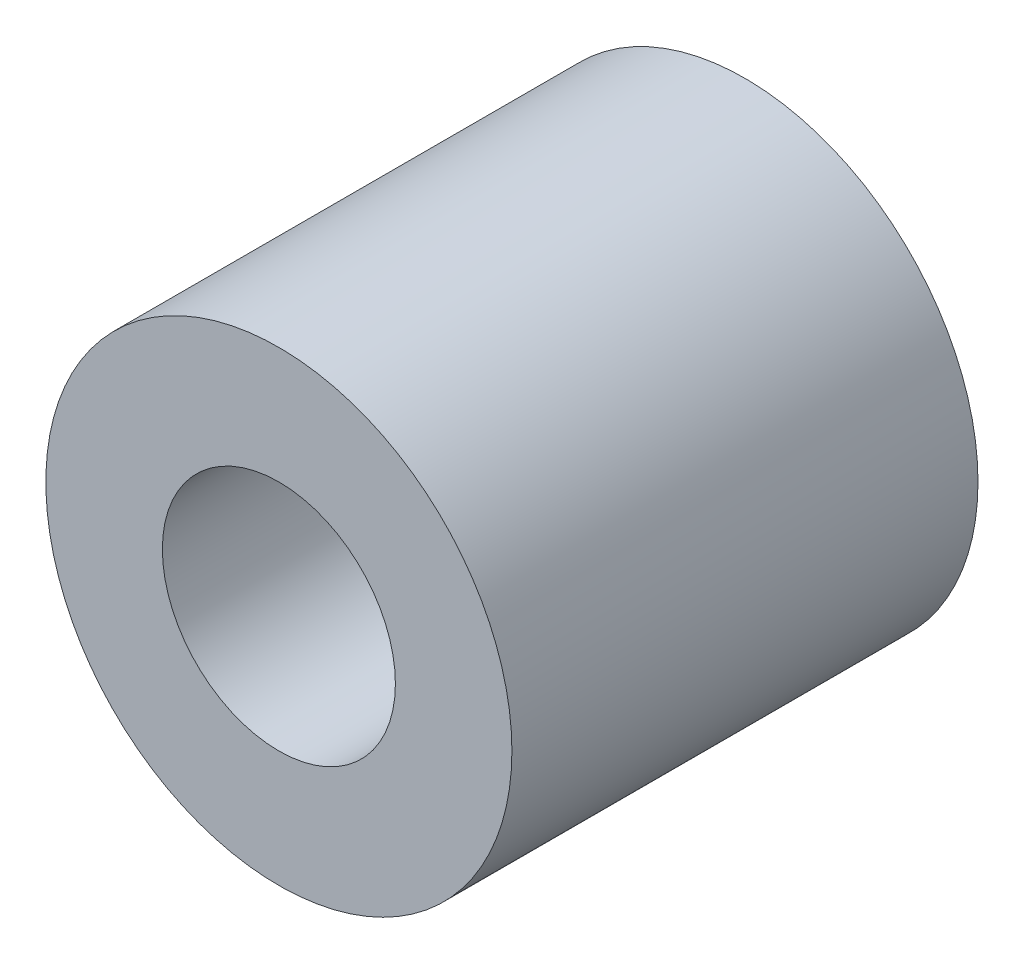
SolidWorks part; units mm, degrees
ref_plane "Front Plane" through (0, 0, 0) normal (0, 0, 1) x (1, 0, 0)
ref_plane "Top Plane" through (0, 0, 0) normal (0, 1, 0) x (1, 0, 0)
ref_plane "Right Plane" through (0, 0, 0) normal (1, 0, 0) x (0, 0, -1)
ref_plane "plane:base-xy" through (0, 0, 0) normal (0, 0, 1) x (1, 0, 0)
sketch "sketch:base-profile" plane through (0, 0, 0) normal (0, 0, 1) x (1, 0, 0)
  circle A0 centre (0, 0) radius 10
extrude "feature:base" add sketch "sketch:base-profile" along normal blind 20 separate body
ref_plane "plane:top-xy" through (0, 0, 20) normal (0, 0, 1) x (1, 0, 0)
sketch "sketch:hole-profile" plane through (0, 0, 20) normal (0, 0, 1) x (1, 0, 0)
  circle A0 centre (0, 0) radius 5
extrude "feature:blind-hole" cut sketch "sketch:hole-profile" against normal blind 10
